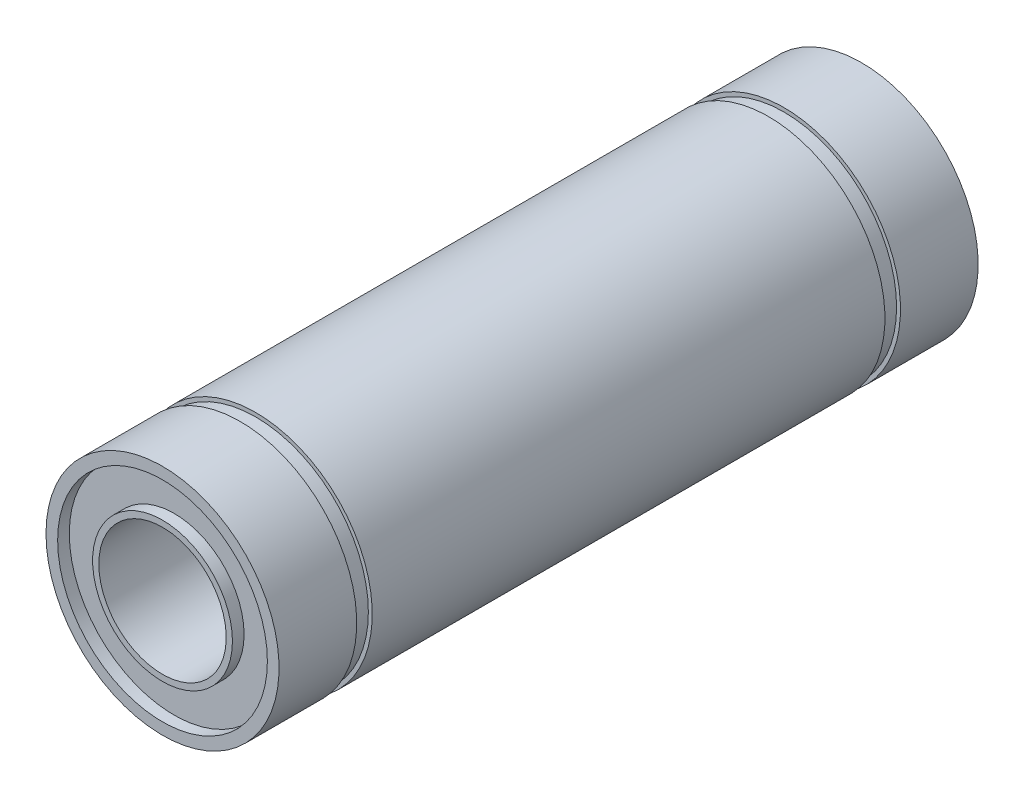
SolidWorks part; units mm, degrees
ref_plane "Front Plane" through (0, 0, 0) normal (0, 0, 1) x (1, 0, 0)
ref_plane "Top Plane" through (0, 0, 0) normal (0, 1, 0) x (1, 0, 0)
ref_plane "Right Plane" through (0, 0, 0) normal (1, 0, 0) x (0, 0, -1)
sketch "Sketch1" plane through (0, 0, 0) normal (0, 0, 1) x (1, 0, 0)
  circle A0 centre (0, 0) radius 4.1
  circle A1 centre (0, 0) radius 7.5
extrude "Boss-Extrude1" add sketch "Sketch1" along normal blind 45
sketch "Sketch2" plane through (0, 0, 45) normal (0, 0, 1) x (1, 0, 0)
  circle A0 centre (0, 0) radius 6.75
  circle A1 centre (0, 0) radius 4.5
extrude "Cut-Extrude2" cut sketch "Sketch2" against normal blind 0.75
sketch "Sketch3" plane through (0, 0, 0) normal (0, 0, -1) x (-1, 0, 0)
  circle A0 centre (0, 0) radius 4.5
  circle A1 centre (0, 0) radius 7
extrude "Cut-Extrude3" cut sketch "Sketch3" against normal blind 0.75
sketch "Sketch4" plane through (0, 0, 0) normal (0, 1, 0) x (1, 0, 0)
  line L0 (-7.5, -45) -> (7.5, -45) construction
  line L1 (-7.5, -40) -> (-7.25, -40)
  line L2 (-7.5, -40) -> (-7.5, -39)
  line L3 (-7.5, -39) -> (-7.25, -39)
  line L4 (-7.25, -40) -> (-7.25, -39)
  line L5 (-7.5, 0) -> (-7.5, -45) construction
  dimension "D1" = 1
  dimension "D2" = 0.25
  dimension "D3" = 5
ref_axis "Axis1" through (0, 0, 45) along (0, 0, -1)
revolve "Cut-Revolve1" cut sketch "Sketch4" angle 360 about axis through (0, 0, 45) along (0, 0, -1)
sketch "Sketch5" plane through (0, 0, 0) normal (0, 1, 0) x (1, 0, 0)
  line L0 (7.5, 0) -> (-7.5, 0) construction
  line L1 (-7.5, -6) -> (-7.25, -6)
  line L2 (-7.5, -6) -> (-7.5, -5)
  line L3 (-7.5, -5) -> (-7.25, -5)
  line L4 (-7.25, -6) -> (-7.25, -5)
  line L5 (-7.5, 0) -> (-7.5, -39) construction
  point P4 (-7.375, -5)
  dimension "D1" = 1
  dimension "D2" = 5
revolve "Cut-Revolve2" cut sketch "Sketch5" angle 360 about axis through (0, 0, 45) along (0, 0, -1)
